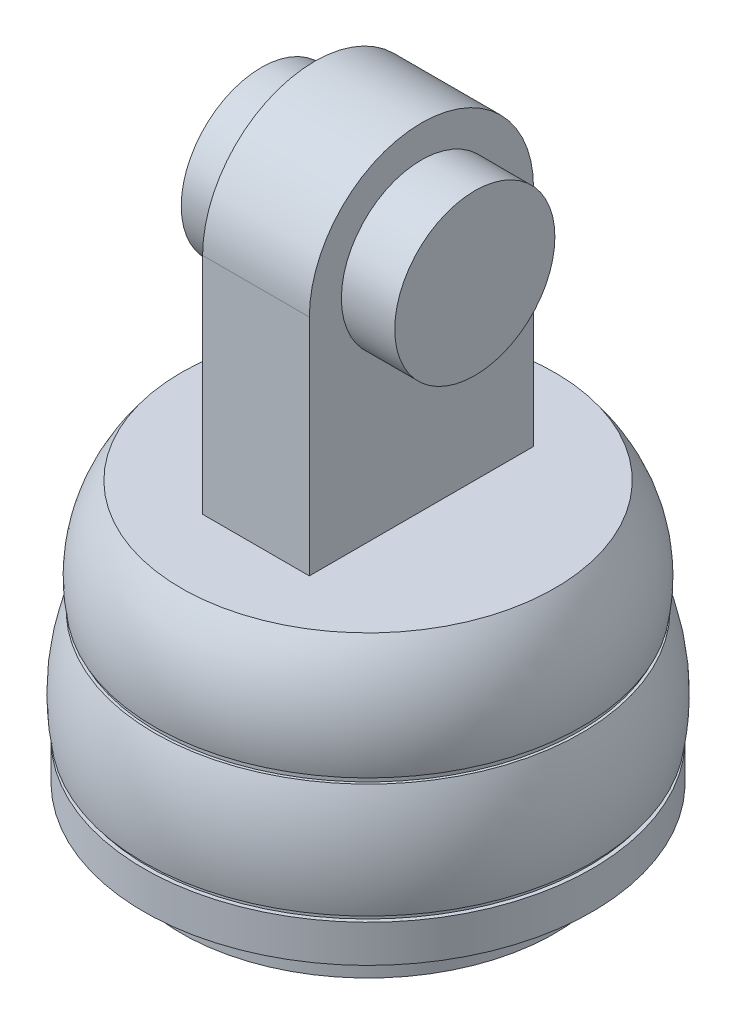
SolidWorks part; units mm, degrees
ref_plane "Front Plane" through (0, 0, 0) normal (0, 0, 1) x (1, 0, 0)
ref_plane "Top Plane" through (0, 0, 0) normal (0, 1, 0) x (1, 0, 0)
ref_plane "Right Plane" through (0, 0, 0) normal (1, 0, 0) x (0, 0, -1)
sketch "Sketch1" plane through (0, 0, 0) normal (0, 0, 1) x (1, 0, 0)
  line L0 (-35, 0) -> (0, 0)
  line L1 (0, 0) -> (0, -20)
  line L2 (0, -20) -> (-40, -20)
  arc A0 (-40, -20) -> (-35, 0) centre (-15.404, -15.524) cw
  dimension "D4" = 25
  dimension "D1" = 35
  dimension "D2" = 20
  dimension "D3" = 40
revolve "Revolve1" add sketch "Sketch1" angle 360 about L1
sketch "Sketch2" plane through (0, -20, 0) normal (0, -1, 0) x (1, 0, 0)
  circle A0 centre (0, 0) radius 39.5
  dimension "D1" = 79
extrude "Boss-Extrude1" add sketch "Sketch2" along normal blind 1
sketch "Sketch3" plane through (0, 0, 0) normal (1, 0, 0) x (0, 0, -1)
  line L0 (0, -21) -> (-40, -21)
  line L1 (-39.5, -21) -> (39.5, -21) construction
  line L2 (0, -21) -> (0, -41)
  line L3 (0, -41) -> (-42, -41)
  arc A0 (-42, -41) -> (-40, -21) centre (-5.5677, -34.5432) cw
  dimension "D4" = 37
  dimension "D1" = 40
  dimension "D2" = 20
  dimension "D3" = 42
revolve "Revolve2" add sketch "Sketch3" angle 360 about L2
sketch "Sketch4" plane through (0, -41, 0) normal (0, -1, 0) x (1, 0, 0)
  circle A0 centre (0, 0) radius 41.25
  dimension "D1" = 82.5
extrude "Boss-Extrude2" add sketch "Sketch4" along normal blind 1
sketch "Sketch5" plane through (0, -42, 0) normal (0, -1, 0) x (1, 0, 0)
  circle A0 centre (0, 0) radius 42
  dimension "D1" = 84
extrude "Boss-Extrude3" add sketch "Sketch5" along normal blind 7
sketch "Sketch6" plane through (0, -49, 0) normal (0, -1, 0) x (1, 0, 0)
  circle A0 centre (0, 0) radius 35
  dimension "D1" = 70
extrude "Boss-Extrude4" add sketch "Sketch6" along normal blind 7
sketch "Sketch7" plane through (0, -49, 0) normal (0, -1, 0) x (1, 0, 0)
  line L1 (38.4461, -2.2339) -> (40.3807, -1.117)
  line L2 (40.3807, -1.117) -> (40.3807, 1.117)
  line L3 (40.3807, 1.117) -> (38.4461, 2.2339)
  line L4 (38.4461, 2.2339) -> (36.5114, 1.117)
  line L5 (36.5114, 1.117) -> (36.5114, -1.117)
  line L6 (36.5114, -1.117) -> (38.4461, -2.2339)
  line L7 (38.4461, -1.5469) -> (39.7857, -0.7735)
  line L8 (39.7857, -0.7735) -> (39.7857, 0.7735)
  line L9 (39.7857, 0.7735) -> (38.4461, 1.5469)
  line L10 (38.4461, 1.5469) -> (37.1064, 0.7735)
  line L11 (37.1064, 0.7735) -> (37.1064, -0.7735)
  line L12 (37.1064, -0.7735) -> (38.4461, -1.5469)
  circle A0 centre (38.4461, 0) radius 1.9347 construction
  circle A1 centre (38.4461, 0) radius 1.3397 construction
extrude "Boss-Extrude5" add sketch "Sketch7" along normal blind 1
pattern_circular "CirPattern1" count 10 over 360 about axis through (0, 0, 0) along (0, 1, 0) of "Boss-Extrude5"
sketch "Sketch9" plane through (0, -56, 0) normal (0, -1, 0) x (1, 0, 0)
  circle A0 centre (0, 0) radius 15
  dimension "D1" = 30
extrude "Boss-Extrude6" add sketch "Sketch9" along normal blind 10
sketch "Sketch10" plane through (0, 0, 0) normal (0, 1, 0) x (1, 0, 0)
  line L0 (0, 21) -> (0, -21) construction
  line L1 (-10, 21) -> (-10, -21)
  line L2 (10, 21) -> (10, -21)
  line L3 (-10, 21) -> (10, 21)
  line L4 (-10, -21) -> (10, -21)
  point P4 (0, 0)
  dimension "D1" = 42
  dimension "D2" = 10
  dimension "D3" = 10
extrude "Boss-Extrude7" add sketch "Sketch10" along normal blind 42
sketch "Sketch11" plane through (10, 0, 0) normal (1, 0, 0) x (0, 0, -1)
  line L0 (-21, 42) -> (21, 42) construction
  line L1 (-21, 42) -> (21, 42)
  arc A0 (21, 42) -> (-21, 42) centre (0, 42) ccw
extrude "Boss-Extrude8" add sketch "Sketch11" against normal up to vertex
sketch "Sketch12" plane through (-10, 0, 0) normal (-1, 0, 0) x (0, 0, 1)
  circle A0 centre (0, 42) radius 15
  dimension "D1" = 30
extrude "Boss-Extrude9" add sketch "Sketch12" along normal blind 10
sketch "Sketch13" plane through (10, 0, 0) normal (1, 0, 0) x (0, 0, -1)
  circle A0 centre (0, 42) radius 15
  dimension "D1" = 30
extrude "Boss-Extrude10" add sketch "Sketch13" along normal blind 10
